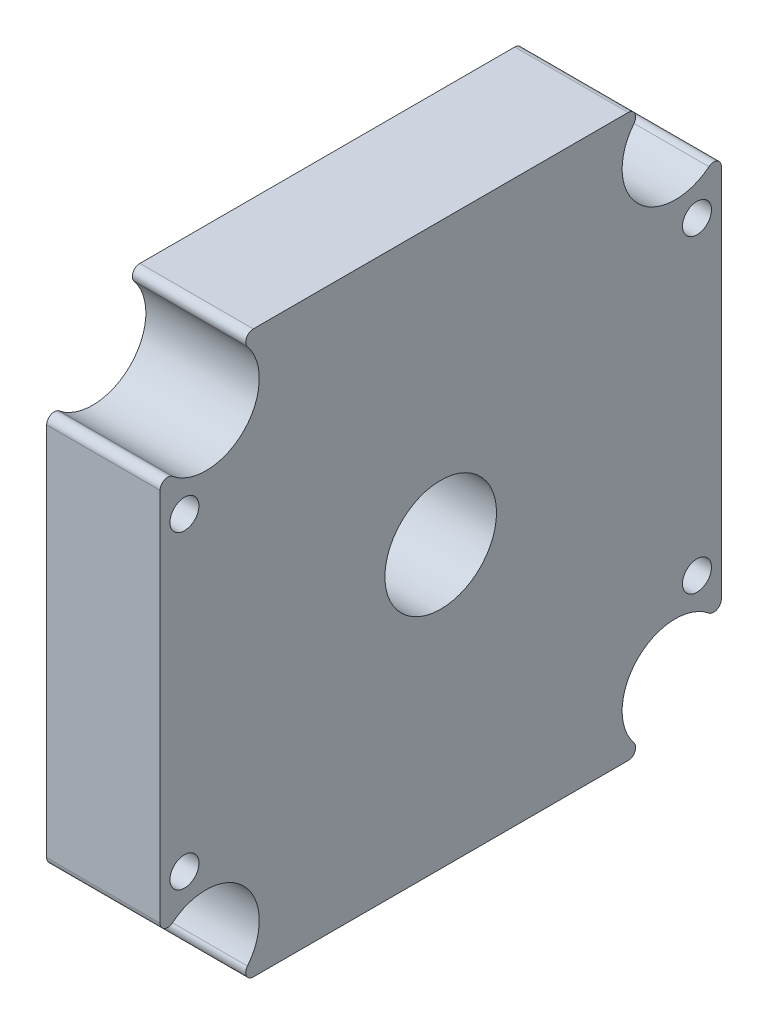
SolidWorks part; units mm, degrees
ref_plane "Front Plane" through (0, 0, 0) normal (0, 0, 1) x (1, 0, 0)
ref_plane "Top Plane" through (0, 0, 0) normal (0, 1, 0) x (1, 0, 0)
ref_plane "Right Plane" through (0, 0, 0) normal (1, 0, 0) x (0, 0, -1)
sketch "Sketch1" plane through (0, 0, 0) normal (1, 0, 0) x (0, 0, -1)
  line L1 (-28.0924, -28.0924) -> (28.0924, -28.0924)
  line L2 (-28.0924, -28.0924) -> (-28.0924, 28.0924)
  line L3 (-28.0924, 28.0924) -> (28.0924, 28.0924)
  line L4 (28.0924, -28.0924) -> (28.0924, 28.0924)
  line L5 (-28.0924, -28.0924) -> (28.0924, 28.0924) construction
  line L6 (-28.0924, 28.0924) -> (28.0924, -28.0924) construction
  point P0 (0, 0)
  dimension "D1" = 56.1848
  dimension "D2" = 56.1848
extrude "Boss-Extrude1" add sketch "Sketch1" along normal blind 11.3538
sketch "Sketch2" plane through (11.3538, 0, 0) normal (1, 0, 0) x (0, 0, -1)
  line L0 (0, 28.0924) -> (0, 0) construction
  line L1 (28.0924, 28.0924) -> (-28.0924, 28.0924) construction
  line L2 (0, 0) -> (-28.0924, 0) construction
  line L3 (-28.0924, 28.0924) -> (-28.0924, -28.0924) construction
  circle A0 centre (-23.495, 23.495) radius 2.54
  circle A1 centre (23.495, 23.495) radius 2.54
  circle A2 centre (23.495, -23.495) radius 2.54
  circle A3 centre (-23.495, -23.495) radius 2.54
  dimension "D1" = 5.08
  dimension "D2" = 46.99
  dimension "D3" = 46.99
extrude "Cut-Extrude1" cut sketch "Sketch2" against normal through all
fillet "Fillet1" radius 3.175 4 edges at (5.6769, -28.0924, 28.0924) (5.6769, -28.0924, -28.0924) (5.6769, 28.0924, -28.0924) (5.6769, 28.0924, 28.0924)
sketch "Sketch7" plane through (0, 0, 0) normal (-1, 0, 0) x (0, 0, 1)
  circle A0 centre (-23.495, 23.495) radius 5.334
  circle A1 centre (23.495, 23.495) radius 5.334
  circle A2 centre (23.495, -23.495) radius 5.334
  circle A3 centre (-23.495, -23.495) radius 5.334
  dimension "D1" = 10.668
extrude "Cut-Extrude5" cut sketch "Sketch7" against normal through all
fillet "Fillet4" radius 0.762 8 edges at (5.6769, 20.7903, 28.0924) (5.6769, -20.7903, 28.0924) (5.6769, -28.0924, 20.7903) (5.6769, -28.0924, -20.7903) (5.6769, -20.7903, -28.0924) (5.6769, 28.0924, -20.7903) (5.6769, 28.0924, 20.7903) (5.6769, 20.7903, -28.0924)
hole_wizard "M3.5x0.6 Tapped Hole1" positions "Sketch9" profile "Sketch10" tap size "M3.5x0.6" standard "ANSI Metric" end condition through all
sketch "Sketch9" plane through (11.3538, 0, 0) normal (1, 0, 0) x (0, 0, -1)
  line L0 (0, 28.0924) -> (0, 0) construction
  line L1 (18.7568, 28.0924) -> (-18.7568, 28.0924) construction
  line L2 (0, 0) -> (-28.0924, 0) construction
  line L3 (-28.0924, 18.7568) -> (-28.0924, -18.7568) construction
  point P0 (-25.654, 15.494)
  point P17 (25.654, 15.494)
  point P19 (25.654, -15.494)
  point P20 (-25.654, -15.494)
  dimension "D1" = 30.988
  dimension "D2" = 51.308
sketch "Sketch10" plane through (11.3538, 15.494, 25.654) normal (0, 1, 0) x (0, 0, -1)
  line L0 (0, 0) -> (0, 11.3538)
  line L1 (0, 11.3538) -> (1.45, 11.3538)
  line L2 (1.45, 11.3538) -> (1.45, 0)
  line L5 (1.45, 0) -> (0, 0)
  line L11 (0, -6.35) -> (0, 107.95) construction
  dimension "Thru Tap Drill Dia." = 2.9
  dimension "Thru Tap Drill Depth" = 11.3538
cosmetic thread "Hole Thread1" parameters "D2"=3.5
cosmetic thread "Hole Thread2" parameters "D2"=3.5
cosmetic thread "Hole Thread3" parameters "D2"=3.5
cosmetic thread "Hole Thread4" parameters "D2"=3.5
sketch "Sketch11" plane through (11.3538, 0, 0) normal (1, 0, 0) x (0, 0, -1)
  circle A0 centre (0, 0) radius 5.588
  dimension "D1" = 11.176
extrude "Cut-Extrude6" cut sketch "Sketch11" against normal through all
